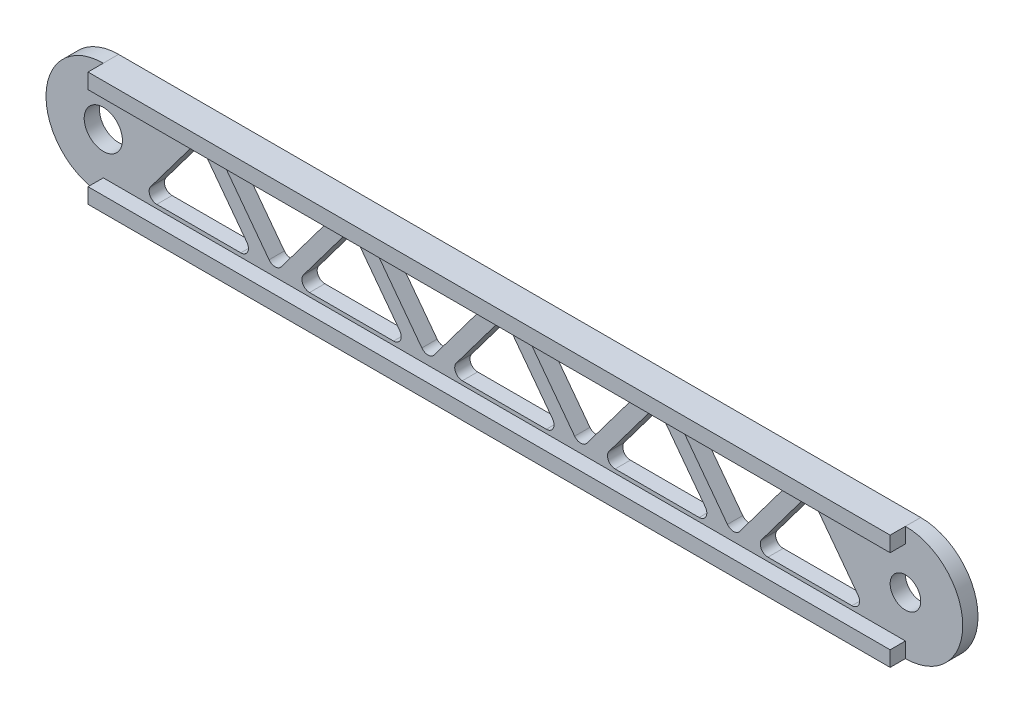
SolidWorks part; units mm, degrees
ref_plane "前视基准面" through (0, 0, 0) normal (0, 0, 1) x (1, 0, 0)
ref_plane "上视基准面" through (0, 0, 0) normal (0, 1, 0) x (1, 0, 0)
ref_plane "右视基准面" through (0, 0, 0) normal (1, 0, 0) x (0, 0, -1)
sketch "草图1" plane through (0, 0, 0) normal (0, 0, 1) x (1, 0, 0)
  line L0 (0, 0) -> (420, 0)
  line L1 (420, 0) -> (420, 60)
  line L2 (420, 60) -> (0, 60)
  line L3 (0, 60) -> (0, 0)
extrude "凸台-拉伸1" add sketch "草图1" along normal blind 8
sketch "草图2" plane through (0, 0, 0) normal (0, 0, 1) x (1, 0, 0)
  circle A0 centre (0, 30) radius 30
  circle A1 centre (420, 30) radius 30
extrude "凸台-拉伸2" add sketch "草图2" along normal blind 8
ref_plane "基准面1" through (0, 0, 8) normal (0, 0, 1) x (1, 0, 0)
sketch "草图3" plane through (0, 0, 8) normal (0, 0, 1) x (1, 0, 0)
  line L0 (0, 0) -> (420, 0)
  line L1 (420, 0) -> (420, 8)
  line L2 (420, 8) -> (0, 8)
  line L3 (0, 8) -> (0, 0)
  line L4 (0, 52) -> (420, 52)
  line L5 (420, 52) -> (420, 60)
  line L6 (420, 60) -> (0, 60)
  line L7 (0, 60) -> (0, 52)
extrude "凸台-拉伸3" add sketch "草图3" along normal blind 8
sketch "草图4" plane through (0, 0, 8) normal (0, 0, 1) x (1, 0, 0)
  circle A0 centre (0, 30) radius 10
extrude "切除-拉伸1" cut sketch "草图4" against normal mid plane 962
sketch "草图5" plane through (0, 0, 8) normal (0, 0, 1) x (1, 0, 0)
  circle A0 centre (420, 30) radius 8
extrude "切除-拉伸2" cut sketch "草图5" against normal mid plane 962
sketch "草图6" plane through (0, 0, 0) normal (0, 0, 1) x (1, 0, 0)
  line L0 (28, 10) -> (72, 10)
  line L1 (75.2, 16.4) -> (53.2, 45.7333)
  line L2 (46.8, 45.7333) -> (24.8, 16.4)
  line L3 (108, 10) -> (152, 10)
  line L4 (155.2, 16.4) -> (133.2, 45.7333)
  line L5 (126.8, 45.7333) -> (104.8, 16.4)
  line L6 (188, 10) -> (232, 10)
  line L7 (235.2, 16.4) -> (213.2, 45.7333)
  line L8 (206.8, 45.7333) -> (184.8, 16.4)
  line L9 (268, 10) -> (312, 10)
  line L10 (315.2, 16.4) -> (293.2, 45.7333)
  line L11 (286.8, 45.7333) -> (264.8, 16.4)
  line L12 (348, 10) -> (392, 10)
  line L13 (395.2, 16.4) -> (373.2, 45.7333)
  line L14 (366.8, 45.7333) -> (344.8, 16.4)
  line L15 (68, 50) -> (112, 50)
  line L16 (115.2, 43.6) -> (93.2, 14.2667)
  line L17 (86.8, 14.2667) -> (64.8, 43.6)
  line L18 (148, 50) -> (192, 50)
  line L19 (195.2, 43.6) -> (173.2, 14.2667)
  line L20 (166.8, 14.2667) -> (144.8, 43.6)
  line L21 (228, 50) -> (272, 50)
  line L22 (275.2, 43.6) -> (253.2, 14.2667)
  line L23 (246.8, 14.2667) -> (224.8, 43.6)
  line L24 (308, 50) -> (352, 50)
  line L25 (355.2, 43.6) -> (333.2, 14.2667)
  line L26 (326.8, 14.2667) -> (304.8, 43.6)
  arc A0 (24.8, 16.4) -> (28, 10) centre (28, 14) ccw
  arc A1 (72, 10) -> (75.2, 16.4) centre (72, 14) ccw
  arc A2 (53.2, 45.7333) -> (46.8, 45.7333) centre (50, 43.3333) ccw
  arc A3 (104.8, 16.4) -> (108, 10) centre (108, 14) ccw
  arc A4 (152, 10) -> (155.2, 16.4) centre (152, 14) ccw
  arc A5 (133.2, 45.7333) -> (126.8, 45.7333) centre (130, 43.3333) ccw
  arc A6 (184.8, 16.4) -> (188, 10) centre (188, 14) ccw
  arc A7 (232, 10) -> (235.2, 16.4) centre (232, 14) ccw
  arc A8 (213.2, 45.7333) -> (206.8, 45.7333) centre (210, 43.3333) ccw
  arc A9 (264.8, 16.4) -> (268, 10) centre (268, 14) ccw
  arc A10 (312, 10) -> (315.2, 16.4) centre (312, 14) ccw
  arc A11 (293.2, 45.7333) -> (286.8, 45.7333) centre (290, 43.3333) ccw
  arc A12 (344.8, 16.4) -> (348, 10) centre (348, 14) ccw
  arc A13 (392, 10) -> (395.2, 16.4) centre (392, 14) ccw
  arc A14 (373.2, 45.7333) -> (366.8, 45.7333) centre (370, 43.3333) ccw
  arc A15 (64.8, 43.6) -> (68, 50) centre (68, 46) cw
  arc A16 (112, 50) -> (115.2, 43.6) centre (112, 46) cw
  arc A17 (93.2, 14.2667) -> (86.8, 14.2667) centre (90, 16.6667) cw
  arc A18 (144.8, 43.6) -> (148, 50) centre (148, 46) cw
  arc A19 (192, 50) -> (195.2, 43.6) centre (192, 46) cw
  arc A20 (173.2, 14.2667) -> (166.8, 14.2667) centre (170, 16.6667) cw
  arc A21 (224.8, 43.6) -> (228, 50) centre (228, 46) cw
  arc A22 (272, 50) -> (275.2, 43.6) centre (272, 46) cw
  arc A23 (253.2, 14.2667) -> (246.8, 14.2667) centre (250, 16.6667) cw
  arc A24 (304.8, 43.6) -> (308, 50) centre (308, 46) cw
  arc A25 (352, 50) -> (355.2, 43.6) centre (352, 46) cw
  arc A26 (333.2, 14.2667) -> (326.8, 14.2667) centre (330, 16.6667) cw
extrude "切除-拉伸3" cut sketch "草图6" along normal through all
